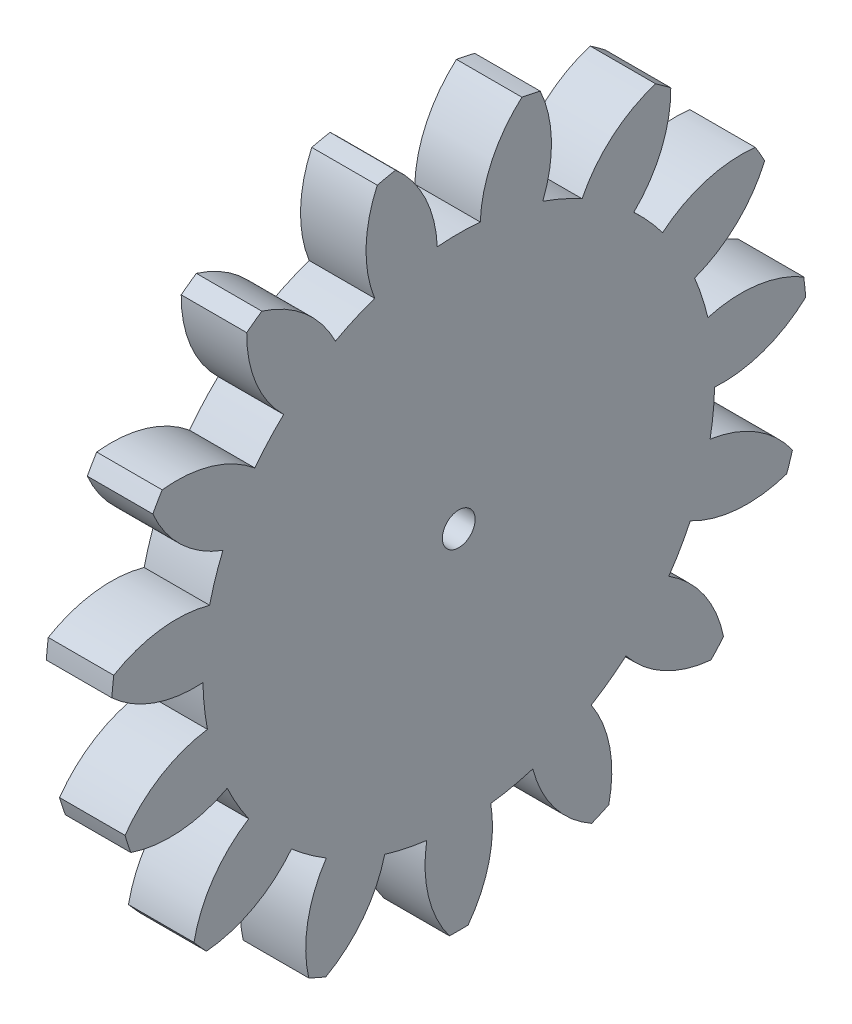
SolidWorks part; units mm, degrees
ref_plane "Plane1" through (0, 0, 0) normal (0, 0, 1) x (1, 0, 0)
ref_plane "Plane2" through (0, 0, 0) normal (0, 1, 0) x (1, 0, 0)
ref_plane "Plane3" through (0, 0, 0) normal (1, 0, 0) x (0, 0, -1)
sketch "HoldingSke" plane through (0, 0, 0) normal (0, 1, 0) x (1, 0, 0)
  line L0 (0, 0) -> (0.1932, -0.0518)
  line L1 (-15, 0) -> (100, 0) construction
  line L2 (0, 0) -> (-2.1039, 2.3779)
  line L3 (0, 0) -> (-11.863, 4.5341)
  line L4 (0, 0) -> (8.3417, 2.2352)
  line L5 (0, 0) -> (-46.8476, -17.4728)
  line L6 (0, 0) -> (-6.6317, -4.4744)
  line L7 (-2.1039, 2.3779) -> (8.6586, 51.2059)
  line L8 (-76.2, 54.61) -> (-75.5, 54.61)
  line L9 (-71.009, 38.7566) -> (-53.1078, 45.2721)
  line L10 (-76.2, 71.12) -> (104.1128, 71.12)
  line L11 (0, 0) -> (-8, 0)
  line L12 (-76.2, 101.6) -> (-76.033, 101.6)
  line L13 (24.9733, 27.94) -> (52.9518, 28.4284)
  line L14 (24.9733, 27.94) -> (24.9743, 27.94)
  line L15 (24.9733, 27.94) -> (100.4006, 29.5858)
  line L16 (-63.627, -5) -> (-12.827, -5)
  circle A0 centre (0, 0) radius 2
  circle A1 centre (0, 0) radius 31.249
  circle A2 centre (0, 0) radius 37.5
  circle A3 centre (0, 0) radius 2
  dimension "Hub_dia" = 75
  dimension "Bore" = 4
  dimension "MBD" = 4
  dimension "Overall_len" = 50
  dimension "Thickness" = 8
  dimension "OAL" = 50.0001
  dimension "T_dim" = 0.7
  dimension "Ap" = 20
  dimension "H" = 19.05
  dimension "Pitch_radius" = 180.3128
  dimension "Width" = 8
  dimension "Addendum_fac" = 1
  dimension "Dedendum_fac" = 1.25
  dimension "Clearance_fac" = 0.25
  dimension "Dedendum_add" = 0.001
sketch "BasProSke" plane through (0, 0, 0) normal (0, 1, 0) x (1, 0, 0)
  line L0 (-10, 0) -> (60, 0) construction
  line L1 (0, 0) -> (0, 42.5)
  line L2 (0, 0) -> (8, 0)
  line L3 (8, 0) -> (8, 42.5)
  line L4 (8, 42.5) -> (0, 42.5)
  dimension "Thickness" = 8
revolve "Base-Revolve" add sketch "BasProSke" angle 360 about L0
sketch "TooCutSke" plane through (0, 0, 0) normal (1, 0, 0) x (0, 0, -1)
  line L1 (0, 0) -> (0, 107) construction
  line L2 (0, 0) -> (-4.2118, 37.2627) construction
  line L3 (0, 0) -> (-15.5202, 73.017) construction
  line L4 (-4.2118, 37.2627) -> (-7.7601, 36.5085) construction
  arc A0 (2.6245, 31.1386) -> (-2.6245, 31.1386) centre (0, 0) ccw
  arc A1 (7.7397, 41.8152) -> (-7.7397, 41.8152) centre (0, 0) ccw
  circle A2 centre (0, 0) radius 37.5 construction
  circle A3 centre (0, 0) radius 35.2385 construction
  arc A4 (-2.6245, 31.1386) -> (-7.7397, 41.8152) centre (-17.6118, 30.5217) ccw
  arc A5 (7.7397, 41.8152) -> (2.6245, 31.1386) centre (17.6118, 30.5217) ccw
extrude "ToothCut" cut sketch "TooCutSke" along normal through all
fillet "Breaks" [suppressed] radius 0.1
fillet "RootFillets" [suppressed] radius 1.251
pattern_circular "TeethCuts" count 15 every 24 about axis through (-10, 0, 0) along (1, 0, 0) of "ToothCut", "RootFillets", "Breaks"
sketch "HubNeaOneSke" plane through (0, 0, 0) normal (-1, 0, 0) x (0, 0, 1)
  circle A0 centre (0, 0) radius 31.249
extrude "HubNearOne" [suppressed] add sketch "HubNeaOneSke" along normal blind 42.0001
sketch "HubNeaBotSke" plane through (0, 0, 0) normal (-1, 0, 0) x (0, 0, 1)
  circle A0 centre (0, 0) radius 31.249
extrude "HubNearBoth" [suppressed] add sketch "HubNeaBotSke" along normal blind 21
ref_plane "FarPln" through (8, 0, 0) normal (1, 0, 0) x (0, 0, -1)
sketch "HubFarSke" plane through (8, 0, 0) normal (1, 0, 0) x (0, 0, -1)
  circle A0 centre (0, 0) radius 31.249
extrude "HubFar" [suppressed] add sketch "HubFarSke" along normal blind 21
sketch "BorSke" plane through (0, 0, 0) normal (1, 0, 0) x (0, 0, -1)
  circle A0 centre (0, 0) radius 2
  dimension "Diameter" = 4
extrude "Bore" cut sketch "BorSke" along normal mid plane 100.0001
sketch "KeySke" plane through (0, 0, 0) normal (1, 0, 0) x (0, 0, -1)
  line L0 (-0.8, 0) -> (-0.8, 2.7)
  line L1 (-0.8, 2.7) -> (0.8, 2.7)
  line L2 (0.8, 2.7) -> (0.8, 0)
  line L3 (0, 0) -> (0, 34) construction
  line L4 (-0.8, 0) -> (0.8, 0)
  dimension "Offset" = 2.7
  dimension "Width" = 1.6
extrude "Keyway" [suppressed] cut sketch "KeySke" along normal mid plane 100.0001
pattern_circular "Keyway2" [suppressed] count 2 every 90 about axis through (-10, 0, 0) along (1, 0, 0)
equation "' \"Module@HoldingSke\" = 6.35"
equation "' \"Num_teeth@HoldingSke\" = 12"
equation "' \"Ap@HoldingSke\" =  20"
equation "' \"Ap@HoldingSke\" = 20"
equation "' \"Width@HoldingSke\" = 0.5 * 25.4"
equation "' \"Hub_dia@HoldingSke\"= 1 * 25.4"
equation "' \"Hub_dia@HoldingSke\" = 1 * 25.4"
equation "' \"Overall_len@HoldingSke\" = 1.0 * 25.4"
equation "' \"Bore@HoldingSke\" = 0.75 * 25.4"
equation "' \"T_dim@HoldingSke\" = 0.1 * 25.4"
equation "' \"Width@KeySke\" = 0.25 * 25.4"
equation "' \"Show_teeth@HoldingSke\" = 13"
equation "' \"Backlash@HoldingSke\" = 0.009 * 25.4"
equation "' \"Addendum_fac@HoldingSke\" = 1.0"
equation "' \"Dedendum_fac@HoldingSke\" = 1.25"
equation "' \"Dedendum_add@HoldingSke\" = 0.00005 * 25.4"
equation "' \"Clearance_fac@HoldingSke\" = 0.25"
equation "\"Pitch@HoldingSke\" = 1 / \"Module@HoldingSke\""
equation "\"Overcut_dia@TooCutSke\" = (\"Num_teeth@HoldingSke\" + 2 * \"Addendum_fac@HoldingSke\") / \"Pitch@HoldingSke\" + 0.002 * 25.4"
equation "\"Pitch_dia@TooCutSke\" = \"Num_teeth@HoldingSke\" / \"Pitch@HoldingSke\""
equation "\"Base_dia@TooCutSke\" = \"Num_teeth@HoldingSke\" / \"Pitch@HoldingSke\" * cos((\"Ap@HoldingSke\"  * 3.14159265 / 180))"
equation "\"Root_dia@TooCutSke\" = (\"Num_teeth@HoldingSke\" + 2) / \"Pitch@HoldingSke\" - 2 * (\"Addendum_fac@HoldingSke\" + \"Dedendum_fac@HoldingSke\") / \"Pitch@HoldingSke\" - \"Dedendum_add@HoldingSke\" * 2"
equation "\"Half_ang@TooCutSke\" = 180 / \"Num_teeth@HoldingSke\""
equation "\"Half_CT@TooCutSke\" = \"Num_teeth@HoldingSke\" / \"Pitch@HoldingSke\" * sin((3.14159265 / 2 / \"Num_teeth@HoldingSke\")) / 2 - 7 * \"Backlash@HoldingSke\" / 4"
equation "\"Flank_rad@TooCutSke\" = \"Num_teeth@HoldingSke\" / \"Pitch@HoldingSke\" / 5"
equation "\"Radius@RootFillets\" = \"Clearance_fac@HoldingSke\" / \"Pitch@HoldingSke\" + \"Dedendum_add@HoldingSke\""
equation "\"Break_rad@Breaks\" = 0.02 / \"Pitch@HoldingSke\""
equation "\"Thickness@HoldingSke\" = \"Width@HoldingSke\""
equation "\"OAL@HoldingSke\" = \"Thickness@HoldingSke\""
equation "\"MHD@HoldingSke\" = (\"Num_teeth@HoldingSke\" + 2) / \"Pitch@HoldingSke\" - 2 * (\"Addendum_fac@HoldingSke\" + \"Dedendum_fac@HoldingSke\")  / \"Pitch@HoldingSke\" - \"Dedendum_add@HoldingSke\" * 2"
equation "\"MBD@HoldingSke\" = (\"Num_teeth@HoldingSke\" + 2) / \"Pitch@HoldingSke\" - 2 * (\"Addendum_fac@HoldingSke\" + \"Dedendum_fac@HoldingSke\")  / \"Pitch@HoldingSke\" - \"Dedendum_add@HoldingSke\" * 2 - 0.002 * 25.4"
equation "\"MHD@HoldingSke\" = ((sgn( \"MHD@HoldingSke\" - \"Hub_dia@HoldingSke\" )-1)*( \"MHD@HoldingSke\" - \"Hub_dia@HoldingSke\" ))/-2+ \"Hub_dia@HoldingSke\""
equation "\"MBD@HoldingSke\" = ((sgn( \"MBD@HoldingSke\" - \"Bore@HoldingSke\" )-1)*( \"MBD@HoldingSke\" - \"Bore@HoldingSke\" ))/-2+ \"Bore@HoldingSke\""
equation "\"OAL@HoldingSke\" = ((sgn( \"OAL@HoldingSke\" - \"Overall_len@HoldingSke\" )+1)*( \"OAL@HoldingSke\" - \"Overall_len@HoldingSke\" ))/2 + \"Overall_len@HoldingSke\" + 0.000002 * 25.4"
equation "\"Num_teeth@TeethCuts\" = int( \"Show_teeth@HoldingSke\" ) + 1"
equation "\"Num_teeth@TeethCuts\" = ((sgn( \"Num_teeth@TeethCuts\" - \"Num_teeth@HoldingSke\" )-1)*( \"Num_teeth@TeethCuts\" - \"Num_teeth@HoldingSke\" ))/-2+ \"Num_teeth@HoldingSke\""
equation "\"Num_teeth@TeethCuts\" = ((sgn( \"Num_teeth@TeethCuts\" - 2.0)+1)*( \"Num_teeth@TeethCuts\" - 2.0))/2 +2.0"
equation "\"Angle@TeethCuts\" = 360.0 / \"Num_teeth@HoldingSke\""
equation "\"Diameter@BasProSke\" = (\"Num_teeth@HoldingSke\" + 2 * \"Addendum_fac@HoldingSke\") / \"Pitch@HoldingSke\""
equation "\"Thickness@BasProSke\"  = \"Thickness@HoldingSke\""
equation "' \"Fillet_rad@BasProSke\" =  \"Thickness@HoldingSke\" * 0.05"
equation "' \"Fillet_rad@BasProSke\" = \"Thickness@HoldingSke\" * 0.05"
equation "\"MHD@HoldingSke\" = ((sgn( \"MHD@HoldingSke\" - \"Root_dia@TooCutSke\" )-1)*( \"MHD@HoldingSke\" - \"Root_dia@TooCutSke\" ))/-2+ \"Root_dia@TooCutSke\""
equation "\"Diameter@HubNeaOneSke\" = \"MHD@HoldingSke\""
equation "\"Length@HubNearOne\" = \"OAL@HoldingSke\" - \"Thickness@BasProSke\""
equation "\"Diameter@HubNeaBotSke\" = \"MHD@HoldingSke\""
equation "\"Length@HubNearBoth\" = ( \"OAL@HoldingSke\" - \"Thickness@BasProSke\" ) / 2.0"
equation "\"Thickness@FarPln\" = \"Thickness@BasProSke\""
equation "\"Diameter@HubFarSke\" = \"MHD@HoldingSke\""
equation "\"Length@HubFar\" = ( \"OAL@HoldingSke\" - \"Thickness@BasProSke\" ) / 2.0"
equation "\"Diameter@BorSke\" = \"MBD@HoldingSke\""
equation "\"D1@Bore\" = \"OAL@HoldingSke\" * 2.0"
equation "\"D1@Keyway\" = \"OAL@HoldingSke\" * 2.0"
equation "\"Offset@KeySke\" = \"T_dim@HoldingSke\" + \"MBD@HoldingSke\" / 2.0"
